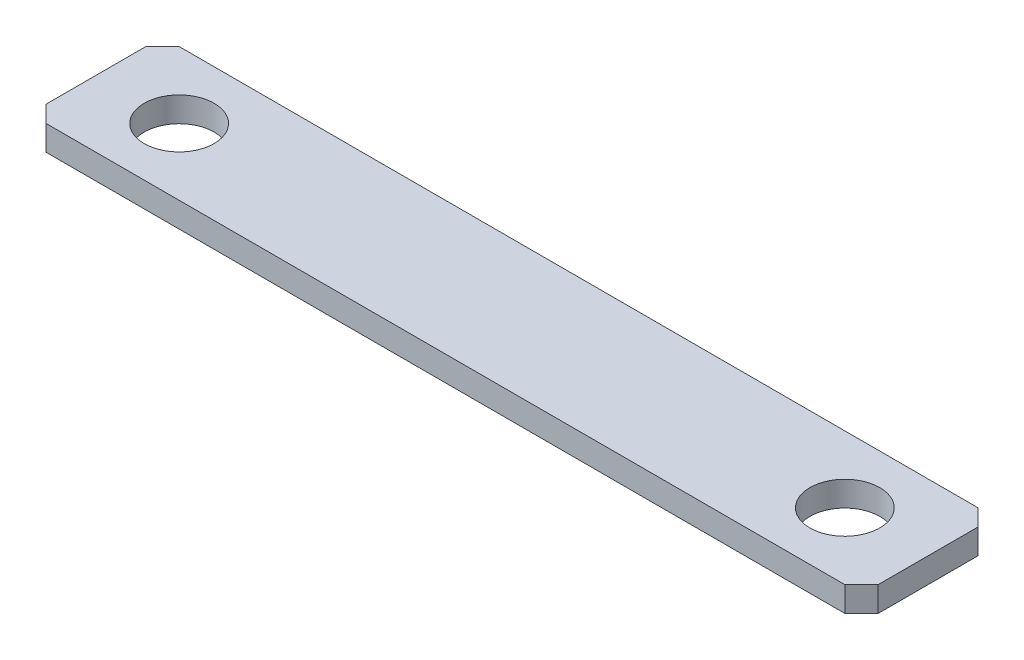
SolidWorks part; units mm, degrees
material "Thornel Mat VMA"
ref_plane "前视基准面" through (0, 0, 0) normal (0, 0, 1) x (1, 0, 0)
ref_plane "上视基准面" through (0, 0, 0) normal (0, 1, 0) x (1, 0, 0)
ref_plane "右视基准面" through (0, 0, 0) normal (1, 0, 0) x (0, 0, -1)
sketch "草图1" plane through (0, 0, 0) normal (0, 1, 0) x (1, 0, 0)
  line L1 (-25, 4) -> (25, 4)
  line L2 (-25, 4) -> (-25, -4)
  line L3 (-25, -4) -> (25, -4)
  line L4 (25, 4) -> (25, -4)
  line L5 (-25, 4) -> (25, -4) construction
  line L6 (-25, -4) -> (25, 4) construction
  point P0 (0, 0)
  dimension "D1" = 8
  dimension "D2" = 50
extrude "凸台-拉伸1" add sketch "草图1" along normal blind 1.5
sketch "草图2" plane through (0, 1.5, 0) normal (0, 1, 0) x (1, 0, 0)
  line L0 (-34.0473, 0) -> (0, 0) construction
  line L1 (0, 0) -> (0, 18.8264) construction
  circle A0 centre (-20, 0) radius 2.1
  circle A1 centre (20, 0) radius 2.1
  point P6 (-34.0473, 0)
  dimension "D1" = 4.2
  dimension "D2" = 40
extrude "切除-拉伸1" cut sketch "草图2" against normal through all
chamfer "倒角1" distance 1 angle 45 4 edges at (25, 0.75, 4) (25, 0.75, -4) (-25, 0.75, -4) (-25, 0.75, 4)
